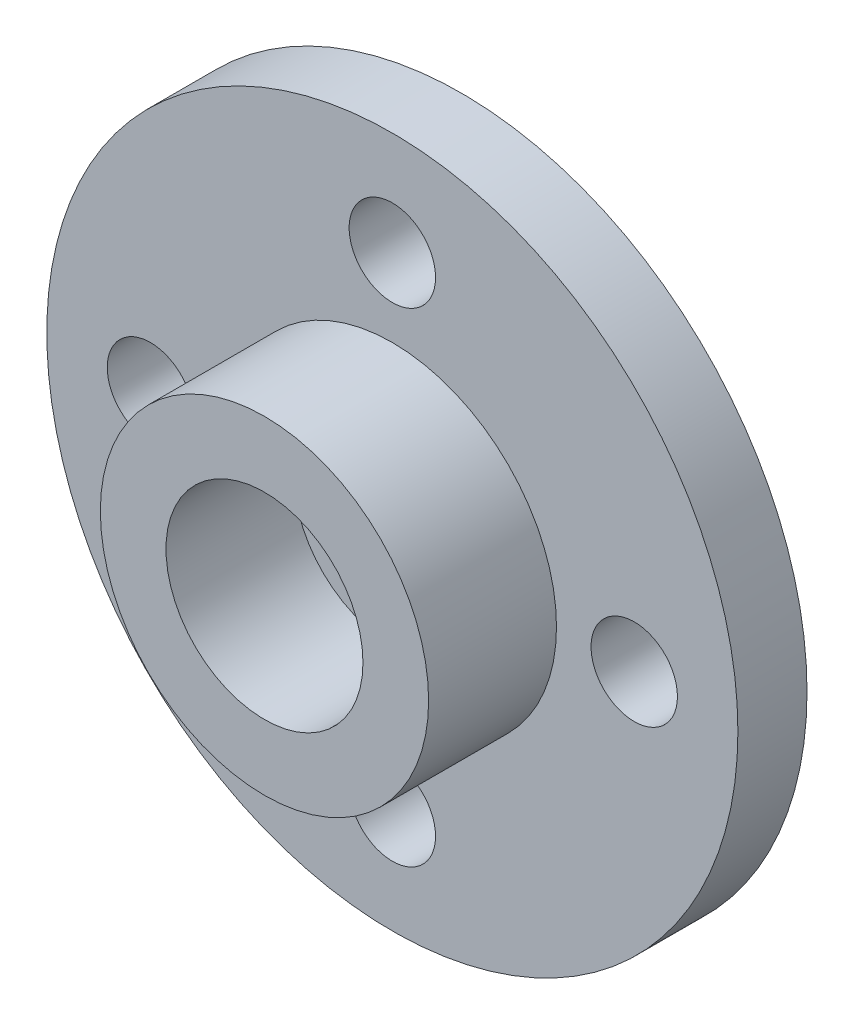
SolidWorks part; units mm, degrees
ref_plane "Plan de face" through (0, 0, 0) normal (0, 0, 1) x (1, 0, 0)
ref_plane "Plan de dessus" through (0, 0, 0) normal (0, 1, 0) x (1, 0, 0)
ref_plane "Plan de droite" through (0, 0, 0) normal (1, 0, 0) x (0, 0, -1)
sketch "Esquisse1" plane through (0, 0, 0) normal (0, 0, 1) x (1, 0, 0)
  circle A0 centre (0, 0) radius 10
  circle A1 centre (0, 0) radius 1.65
  circle A2 centre (0, 7) radius 1.25
  circle A3 centre (7, 0) radius 1.25
  circle A4 centre (0, -7) radius 1.25
  circle A5 centre (-7, 0) radius 1.25
  point P15 (0, 0)
  dimension "D1" = 20
  dimension "D2" = 3.3
  dimension "D3" = 2.5
  dimension "D4" = 7
  dimension "D5" = 4
extrude "Boss.-Extru.1" add sketch "Esquisse1" along normal blind 2
sketch "Esquisse2" plane through (0, 0, 2) normal (0, 0, 1) x (1, 0, 0)
  circle A0 centre (0, 0) radius 4.75
  circle A1 centre (0, 0) radius 2.85
  dimension "D1" = 9.5
  dimension "D2" = 5.7
extrude "Boss.-Extru.2" add sketch "Esquisse2" along normal blind 3.7
